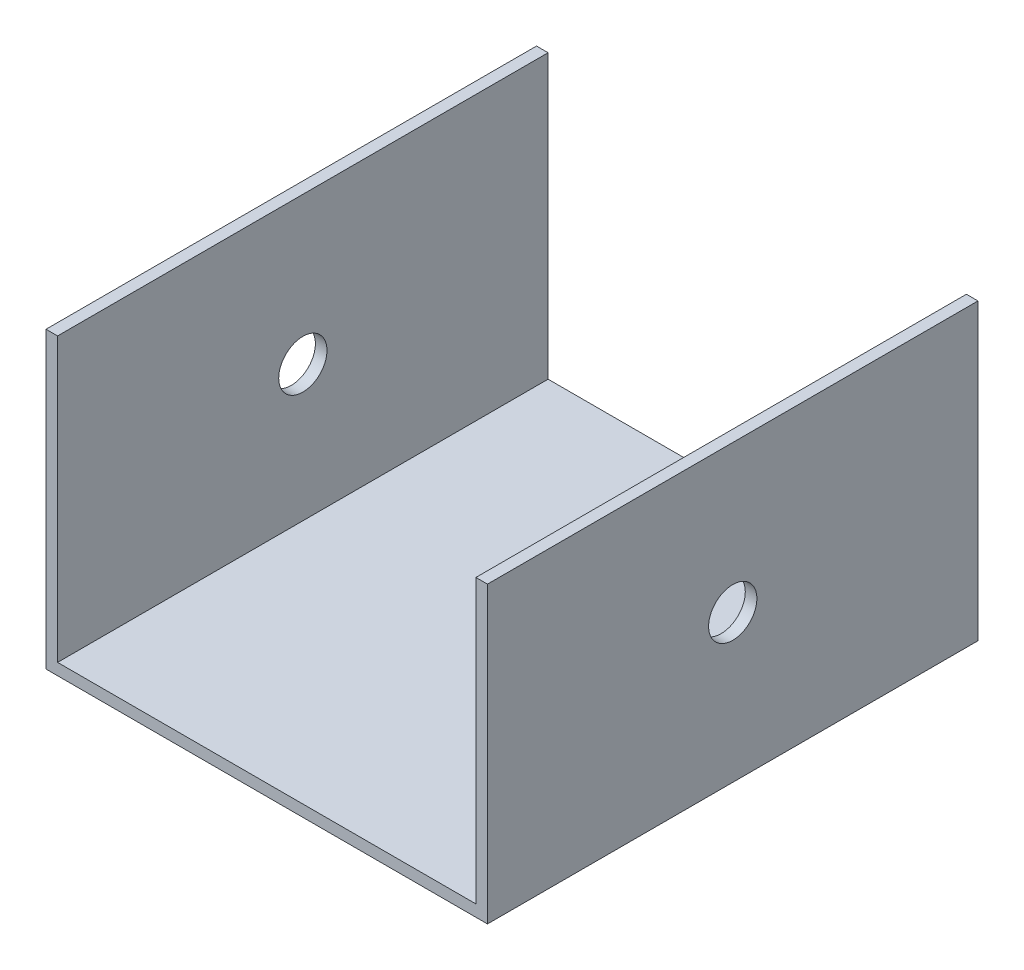
SolidWorks part; units mm, degrees
ref_plane "Front Plane" through (0, 0, 0) normal (0, 0, 1) x (1, 0, 0)
ref_plane "Top Plane" through (0, 0, 0) normal (0, 1, 0) x (1, 0, 0)
ref_plane "Right Plane" through (0, 0, 0) normal (1, 0, 0) x (0, 0, -1)
sketch "Sketch1" plane through (0, 0, 0) normal (0, 0, 1) x (1, 0, 0)
  line L0 (54.15, -35.1) -> (54.15, 38.1)
  line L1 (-57.15, -38.1) -> (57.15, -38.1)
  line L2 (-57.15, -38.1) -> (-57.15, 38.1)
  line L4 (57.15, -38.1) -> (57.15, 38.1)
  line L5 (-54.15, -35.1) -> (54.15, -35.1)
  line L6 (-54.15, -35.1) -> (-54.15, 38.1)
  line L7 (-57.15, 38.1) -> (-54.15, 38.1)
  line L8 (54.15, 38.1) -> (57.15, 38.1)
  point P0 (0, 0)
  dimension "D1" = 76.2
  dimension "D2" = 114.3
  dimension "D3" = 57.15
  dimension "D4" = 57.15
  dimension "D5" = 3
extrude "Boss-Extrude1" add sketch "Sketch1" along normal blind 127
sketch "Sketch2" plane through (0, -35.1, 0) normal (0, 1, 0) x (1, 0, 0)
  line L0 (0, 0) -> (0, -127) construction
  line L1 (54.15, -127) -> (-54.15, -127) construction
  line L2 (-52.6397, -63.5) -> (52.6397, -63.5) construction
  point P8 (0, -63.5)
  point P10 (0, -63.5)
hole_wizard "Ø12.5 (12.5) Diameter Hole1" positions "Sketch2" profile "Sketch3" hole size "Ø12.5" standard "ANSI Metric" end condition through all
sketch "Sketch3" plane through (0, -35.1, 63.5) normal (1, 0, 0) x (0, 0, 1)
  line L0 (0, 0) -> (0, 3)
  line L1 (0, 3) -> (6.25, 3)
  line L2 (6.25, 3) -> (6.25, 0)
  line L5 (6.25, 0) -> (0, 0)
  line L11 (0, -6.35) -> (0, 107.95) construction
  dimension "Thru Hole Dia." = 12.5
  dimension "Thru Hole Depth" = 3
hole_wizard "Ø12.5 (12.5) Diameter Hole2" positions "Sketch5" profile "Sketch6" hole size "Ø12.5" standard "ANSI Metric" end condition through all
sketch "Sketch5" plane through (-57.15, 0, 0) normal (-1, 0, 0) x (0, 0, 1)
  point P0 (63.5, 0)
sketch "Sketch6" plane through (-57.15, 0, 63.5) normal (0, 1, 0) x (0, 0, 1)
  line L0 (0, 0) -> (0, 114.3)
  line L1 (0, 114.3) -> (6.25, 114.3)
  line L2 (6.25, 114.3) -> (6.25, 0)
  line L5 (6.25, 0) -> (0, 0)
  line L11 (0, -6.35) -> (0, 107.95) construction
  dimension "Thru Hole Dia." = 12.5
  dimension "Thru Hole Depth" = 114.3
sketch "Sketch7" plane through (0, -35.1, 0) normal (0, 1, 0) x (1, 0, 0)
  line L0 (54.15, 0) -> (9.7, 0) construction
  line L1 (54.15, 0) -> (-54.15, 0) construction
  line L2 (9.7, 0) -> (9.7, -186.48)
  line L3 (54.15, -127) -> (-54.15, -127) construction
  dimension "D1" = 44.45
  dimension "D2" = 59.48
sketch "Sketch8" plane through (0, -35.1, 0) normal (0, 1, 0) x (1, 0, 0)
  line L3 (-9.7, 0) -> (-9.7, -186.48)
